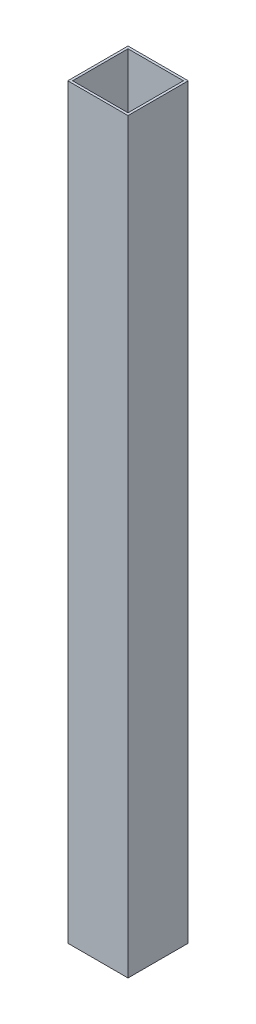
SolidWorks part; units mm, degrees
ref_plane "Front Plane" through (0, 0, 0) normal (0, 0, 1) x (1, 0, 0)
ref_plane "Top Plane" through (0, 0, 0) normal (0, 1, 0) x (1, 0, 0)
ref_plane "Right Plane" through (0, 0, 0) normal (1, 0, 0) x (0, 0, -1)
sketch "Sketch1" plane through (0, 25, 0) normal (0, 1, 0) x (1, 0, 0)
  line L1 (-19.4156, -25) -> (-44.4156, -25)
  line L2 (-19.4156, -25) -> (-19.4156, 0)
  line L3 (-19.4156, 0) -> (-44.4156, 0)
  line L4 (-44.4156, -25) -> (-44.4156, 0)
  line L5 (-20.4156, -24) -> (-43.4156, -24)
  line L6 (-20.4156, -24) -> (-20.4156, -1)
  line L7 (-20.4156, -1) -> (-43.4156, -1)
  line L8 (-43.4156, -24) -> (-43.4156, -1)
extrude "Boss-Extrude1" add sketch "Sketch1" along normal blind 310
